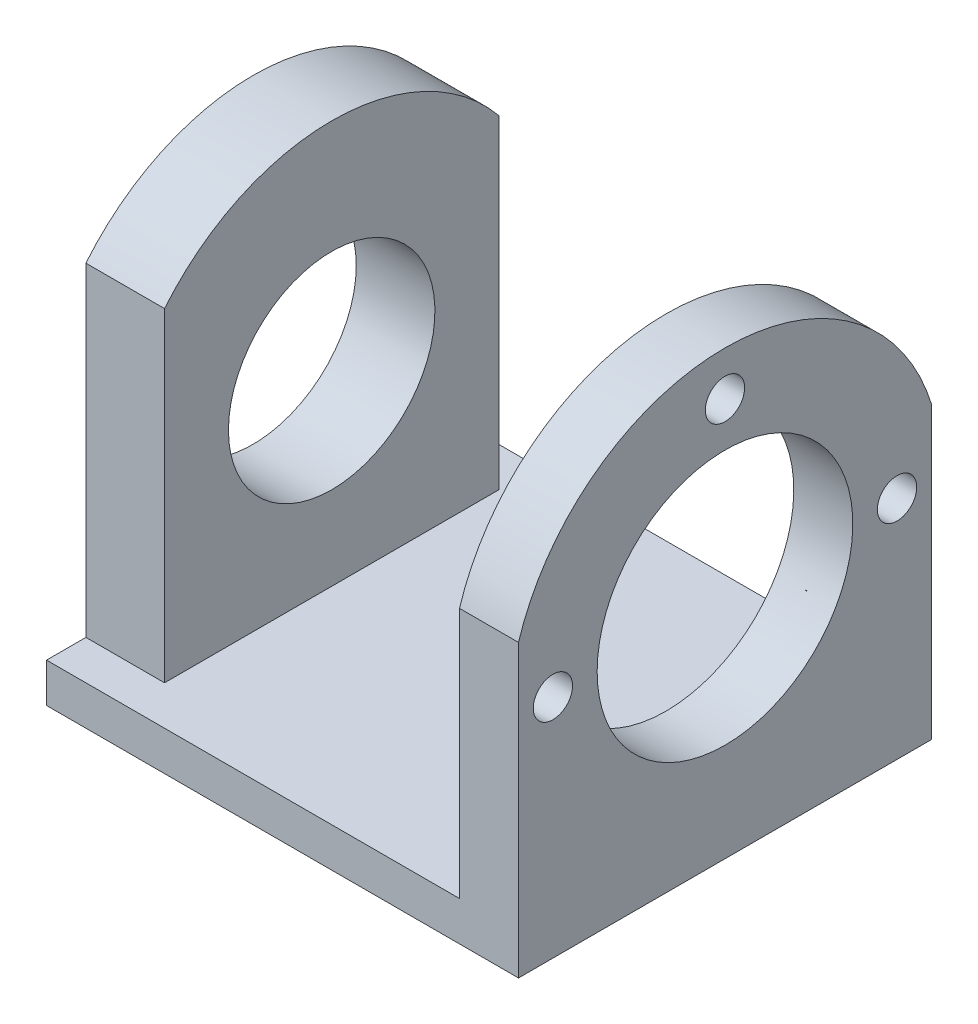
SolidWorks part; units mm, degrees
material "6061 合金"
ref_plane "前视基准面" through (0, 0, 0) normal (0, 0, 1) x (1, 0, 0)
ref_plane "上视基准面" through (0, 0, 0) normal (0, 1, 0) x (1, 0, 0)
ref_plane "右视基准面" through (0, 0, 0) normal (1, 0, 0) x (0, 0, -1)
sketch "草图1" plane through (0, 0, 0) normal (0, 1, 0) x (1, 0, 0)
  line L1 (-24, 21) -> (24, 21)
  line L2 (-24, 21) -> (-24, -21)
  line L3 (-24, -21) -> (24, -21)
  line L4 (24, 21) -> (24, -21)
  line L5 (0, -21) -> (0, 21) construction
  line L6 (-24, 0) -> (24, 0) construction
  point P0 (0, 0)
  dimension "D1" = 42
  dimension "D2" = 48
extrude "凸台-拉伸1" add sketch "草图1" along normal blind 45
sketch "草图2" plane through (0, 0, 0) normal (0, 0, 1) x (1, 0, 0)
  line L0 (-24, 45) -> (24, 45) construction
  line L1 (-16, 45) -> (18, 45)
  line L2 (-16, 45) -> (-16, 4)
  line L3 (-16, 4) -> (18, 4)
  line L4 (18, 45) -> (18, 4)
  line L5 (24, 45) -> (24, 0) construction
  line L6 (-24, 45) -> (-24, 0) construction
  line L7 (-24, 0) -> (24, 0) construction
  dimension "D1" = 6
  dimension "D2" = 8
  dimension "D3" = 4
extrude "切除-拉伸1" cut sketch "草图2" against normal through all both and the other way through all
sketch "草图3" plane through (-24, 0, 0) normal (-1, 0, 0) x (0, 0, 1)
  line L0 (-21, 0) -> (21, 0) construction
  circle A0 centre (0, 23) radius 10.5
  dimension "D1" = 21
  dimension "D2" = 23
extrude "切除-拉伸2" cut sketch "草图3" against normal up to next
sketch "草图4" plane through (18, 0, 0) normal (-1, 0, 0) x (0, 0, 1)
  circle A0 centre (0, 23) radius 13
  dimension "D1" = 26
extrude "切除-拉伸3" cut sketch "草图4" against normal up to next
sketch "草图5" plane through (24, 0, 0) normal (1, 0, 0) x (0, 0, -1)
  circle A0 centre (0, 23) radius 17.5 construction
  circle A1 centre (17.5, 23) radius 2
  circle A2 centre (0, 5.5) radius 2 construction
  circle A3 centre (-17.5, 23) radius 2
  circle A4 centre (0, 40.5) radius 2
  point P14 (0, 23)
  dimension "D1" = 35
  dimension "D2" = 4
  dimension "D3" = 4
extrude "切除-拉伸4" cut sketch "草图5" against normal up to next
sketch "草图6" plane through (-24, 0, 0) normal (-1, 0, 0) x (0, 0, 1)
  line L0 (21, 29.5574) -> (21, 45)
  line L4 (-21, 0) -> (21, 0)
  line L5 (21, 0) -> (21, 45)
  line L6 (21, 45) -> (-21, 45)
  line L7 (-21, 45) -> (-21, 0)
  line L10 (21, 45) -> (-21, 45)
  line L11 (-21, 45) -> (-21, 29.5574)
  arc A0 (21, 29.5574) -> (-21, 29.5574) centre (0, 23) ccw
  line M7 (21, 0) -> (21, 45)
  line M8 (21, 45) -> (-21, 45)
  line M9 (-21, 45) -> (-21, 0)
  dimension "D1" = 0
extrude "切除-拉伸5" cut sketch "草图6" against normal through all contours A0 M7 M8 | A0 L10 M9
sketch "草图7" plane through (-24, 0, 0) normal (-1, 0, 0) x (0, 0, 1)
  line L0 (-17, 36.9642) -> (-17, 4)
  line L1 (-17, 4) -> (-21, 4)
  line L2 (-21, 29.5574) -> (-21, 0) construction
  line L3 (-21, 0) -> (21, 0) construction
  line L4 (0, 29.5574) -> (0, 4.6985) construction
  line L5 (21, 29.5574) -> (21, 4)
  line L6 (17, 4) -> (21, 4)
  line L7 (-21, 29.5574) -> (-21, 0)
  line L8 (-21, 0) -> (21, 0)
  line L9 (21, 0) -> (21, 29.5574)
  line L10 (-21, 29.5574) -> (-21, 4)
  line L11 (17, 36.9642) -> (17, 4)
  arc A0 (21, 29.5574) -> (-21, 29.5574) centre (0, 23) ccw construction
  arc A1 (17, 36.9642) -> (21, 29.5574) centre (0, 23) cw
  arc A2 (21, 29.5574) -> (-21, 29.5574) centre (0, 23) ccw
  arc A3 (-17, 36.9642) -> (-21, 29.5574) centre (0, 23) ccw
  dimension "D1" = 4
  dimension "D2" = 4
  dimension "D3" = 0
extrude "切除-拉伸6" cut sketch "草图7" against normal up to next
sketch "草图8" plane through (0, 0, 0) normal (0, -1, 0) x (1, 0, 0)
  line L0 (0, 27.9927) -> (0, -30.0803) construction
  line L2 (6.1494, 0) -> (36.2839, 0) construction
  circle A0 centre (21, 12.5) radius 1.5
  circle A1 centre (21, -12.5) radius 1.5
  circle A2 centre (-21, -12.5) radius 1.5
  circle A3 centre (-21, 12.5) radius 1.5
  dimension "D1" = 3
  dimension "D2" = 25
  dimension "D3" = 42
hole_wizard "M3 螺纹孔1" positions "3D草图1" profile "草图9" tap size "M3" standard "GB"
sketch3d "3D草图1"
  point P0 (21, 0, -12.5)
  point P3 (21, 0, 12.5)
  point P6 (-21, 0, 12.5)
  point P9 (-21, 0, -12.5)
sketch "草图9" plane through (21, 0, -12.5) normal (1, 0, 0) x (0, 0, -1)
  line L0 (0, 0) -> (0, 17.2511)
  line L1 (0, 17.2511) -> (1.25, 16.5)
  line L2 (1.25, 16.5) -> (1.25, 0)
  line L5 (1.25, 0) -> (0, 0)
  line L10 (0, 17.2511) -> (-1.25, 16.5) construction
  line L11 (0, -6.35) -> (0, 107.95) construction
  dimension "螺纹孔钻头直径" = 2.5
  dimension "螺纹孔钻头深度" = 16.5
  dimension "导头角度" = 118
cosmetic thread "孔螺蚊线1" parameters "D1"=15, "D2"=3
cosmetic thread "孔螺蚊线2" parameters "D1"=15, "D2"=3
cosmetic thread "孔螺蚊线3" parameters "D1"=15, "D2"=3
cosmetic thread "孔螺蚊线4" parameters "D1"=15, "D2"=3
sketch "草图10" plane through (0, 4, 0) normal (0, 1, 0) x (1, 0, 0)
  line L1 (-15, 12.5) -> (15, 12.5)
  line L2 (-15, 12.5) -> (-15, -12.5)
  line L3 (-15, -12.5) -> (15, -12.5)
  line L4 (15, 12.5) -> (15, -12.5)
  line L5 (0, -12.5) -> (0, 12.5) construction
  line L6 (-15, 0) -> (15, 0) construction
  point P0 (0, 0)
  dimension "D1" = 25
  dimension "D2" = 30
extrude "切除-拉伸7" [suppressed] cut sketch "草图10" against normal blind 10
fillet "圆角1" [suppressed] radius 2
